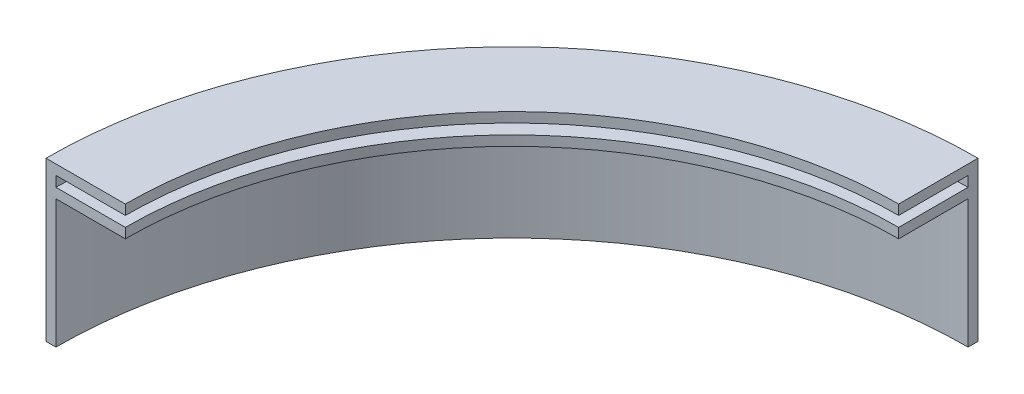
SolidWorks part; units mm, degrees
ref_plane "Front Plane" through (0, 0, 0) normal (0, 0, 1) x (1, 0, 0)
ref_plane "Top Plane" through (0, 0, 0) normal (0, 1, 0) x (1, 0, 0)
ref_plane "Right Plane" through (0, 0, 0) normal (1, 0, 0) x (0, 0, -1)
sketch "Sketch1" plane through (0, 0, 0) normal (0, 0, 1) x (1, 0, 0)
  line L0 (0, 0) -> (0, 50.8)
  line L1 (0, 50.8) -> (25.4, 50.8)
  line L2 (25.4, 50.8) -> (25.4, 47.625)
  line L3 (25.4, 47.625) -> (3.175, 47.625)
  line L4 (3.175, 47.625) -> (3.175, 44.323)
  line L5 (3.175, 44.323) -> (25.4, 44.323)
  line L6 (25.4, 44.323) -> (25.4, 41.148)
  line L7 (25.4, 41.148) -> (3.175, 41.148)
  line L8 (3.175, 41.148) -> (3.175, 0)
  line L9 (3.175, 0) -> (0, 0)
  line L10 (149.225, 38.1) -> (149.225, -0.0155) construction
  dimension "D1" = 3.175
  dimension "D2" = 3.175
  dimension "D3" = 3.175
  dimension "D4" = 3.302
  dimension "D5" = 50.8
  dimension "D6" = 25.4
  dimension "D7" = 22.225
  dimension "D8" = 146.05
revolve "Revolve1" add sketch "Sketch1" angle 90 about L10
equation "\"D2@Sketch1\"=\"D1@Sketch1\""
equation "\"D3@Sketch1\"=\"D1@Sketch1\""
equation "\"D7@Sketch1\"=\"D6@Sketch1\"-\"D1@Sketch1\""
